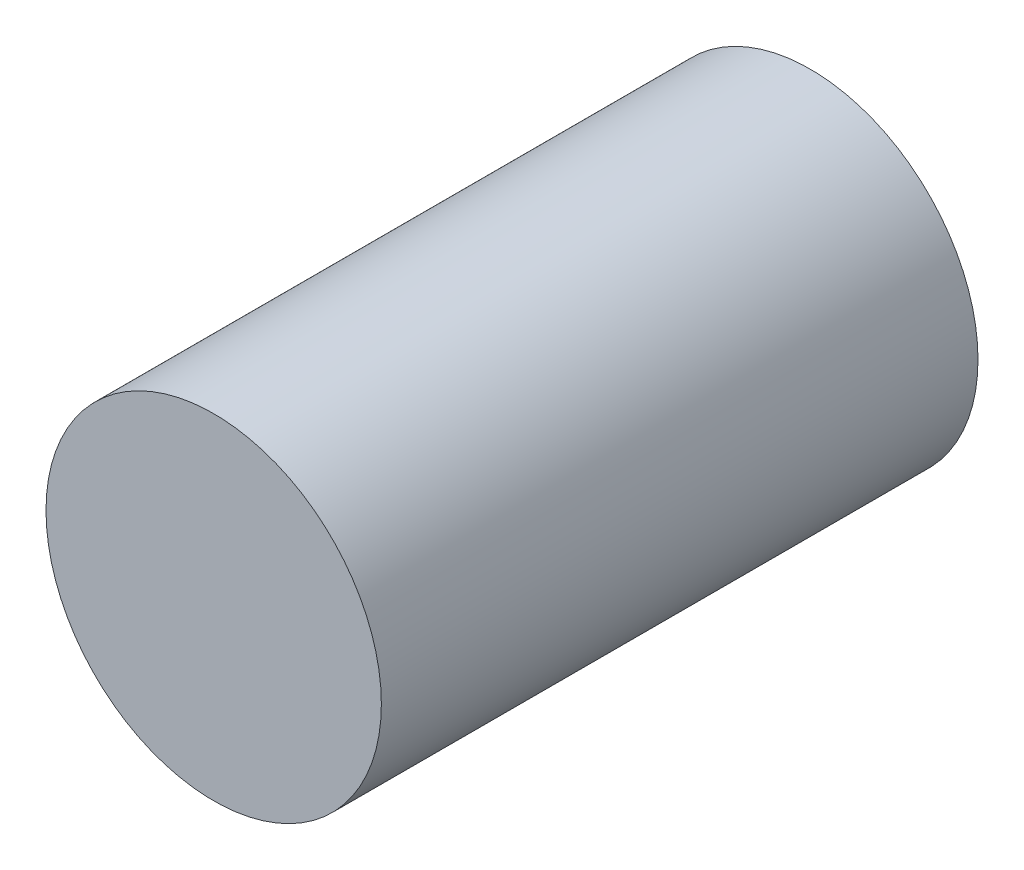
SolidWorks part; units mm, degrees
ref_plane "前视基准面" through (0, 0, 0) normal (0, 0, 1) x (1, 0, 0)
ref_plane "上视基准面" through (0, 0, 0) normal (0, 1, 0) x (1, 0, 0)
ref_plane "右视基准面" through (0, 0, 0) normal (1, 0, 0) x (0, 0, -1)
other "Configuration Table"
sketch "草图1" plane through (0, 0, 0) normal (0, 0, 1) x (1, 0, 0)
  circle A0 centre (0, 0) radius 3.8
  dimension "diameter" = 7.6
extrude "Cable" add sketch "草图1" along normal blind 13.5207
